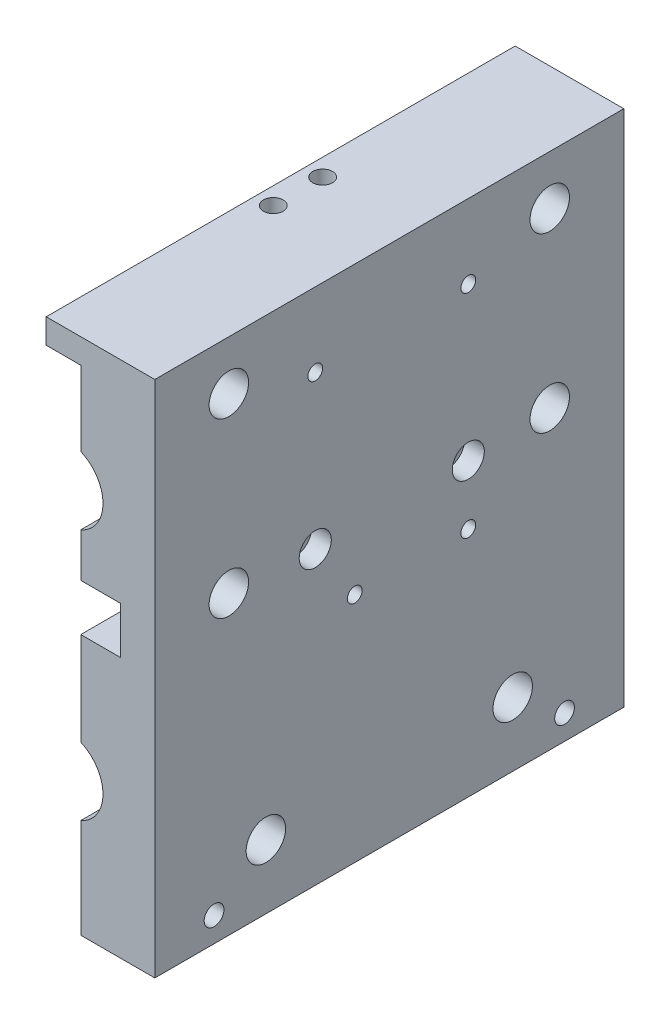
SolidWorks part; units mm, degrees
material "ABS"
ref_plane "Front Plane" through (0, 0, 0) normal (0, 0, 1) x (1, 0, 0)
ref_plane "Top Plane" through (0, 0, 0) normal (0, 1, 0) x (1, 0, 0)
ref_plane "Right Plane" through (0, 0, 0) normal (1, 0, 0) x (0, 0, -1)
sketch "Sketch1" plane through (0, 0, 0) normal (0, 0, 1) x (1, 0, 0)
  line L0 (0, 0) -> (0, -37.75)
  line L1 (0, -37.75) -> (8, -37.75)
  line L2 (8, -37.75) -> (8, -47.25)
  line L3 (8, -47.25) -> (0, -47.25)
  line L4 (0, -47.25) -> (0, -100)
  line L5 (0, -100) -> (15, -100)
  line L6 (15, -100) -> (15, 5)
  line L7 (15, 5) -> (-7, 5)
  line L8 (-7, 5) -> (-7, 0)
  line L9 (-7, 0) -> (0, 0)
  dimension "D1" = 15
  dimension "D2" = 8
  dimension "D3" = 7
  dimension "D4" = 5
  dimension "D5" = 37.75
  dimension "D6" = 105
  dimension "D7" = 9.5
extrude "Boss-Extrude1" add sketch "Sketch1" along normal blind 95
ref_plane "Plan6" through (0, -47.5, 0) normal (0, 1, 0) x (1, 0, 0)
ref_plane "Plan3" through (0, 0, 47.5) normal (0, 0, -1) x (-1, 0, 0)
sketch "Sketch2" plane through (0, 0, 0) normal (-1, 0, 0) x (0, 0, 1)
  line L0 (95, 5) -> (0, 5) construction
  line L2 (47.5, 5) -> (47.5, -173.9913) construction
  line L3 (12.1, -47.5) -> (-12.1, -47.5) construction
  circle A1 centre (62.5, -41) radius 2
  circle A2 centre (31.5, -41) radius 2
  dimension "D2" = 4
  dimension "D4" = 31
  dimension "D5" = 15
  dimension "D6" = 6.5
extrude "Cut-Extrude1 3dprinter4" cut sketch "Sketch2" against normal through all
sketch "Esquisse1" plane through (15, 0, 0) normal (1, 0, 0) x (0, 0, -1)
  line L2 (-47.5, -12.1) -> (-47.5, 12.1) construction
  line L3 (12.1, -47.5) -> (-12.1, -47.5) construction
  circle A0 centre (-62.5, -10) radius 1.5
  circle A1 centre (-31.5, -10) radius 1.5
  circle A4 centre (-54.5, -53) radius 1.5
  circle A5 centre (-31.5, -53) radius 1.5
  dimension "D1" = 15
  dimension "D2" = 37.5
  dimension "D3" = 31
  dimension "D4" = 43
  dimension "D5" = 3
  dimension "D6" = 8
  dimension "D7" = 23
extrude "Enlèv. mat.-Extru.1 3d printer" cut sketch "Esquisse1" against normal through all
sketch "Esquisse2" plane through (0, 0, 0) normal (-1, 0, 0) x (0, 0, 1)
  circle A0 centre (62.5, -10) radius 2.5
  circle A1 centre (31.5, -10) radius 2.5
  dimension "D1" = 5
extrude "Enlèv. mat.-Extru.2" cut sketch "Esquisse2" against normal blind 3 and the other way through all
sketch "Esquisse3" plane through (15, 0, 0) normal (1, 0, 0) x (0, 0, -1)
  circle A1 centre (-31.5, -41) radius 3.25
  circle A2 centre (-62.5, -41) radius 3.25
  dimension "D1" = 6.5
extrude "Enlèv. mat.-Extru.3" cut sketch "Esquisse3" against normal blind 4
sketch "Esquisse4" plane through (15, 0, 0) normal (1, 0, 0) x (0, 0, -1)
  line L0 (-95, -100) -> (-95, 5) construction
  line L1 (0, -100) -> (0, 5) construction
  line L2 (-95, -100) -> (0, -100) construction
  circle A0 centre (-83, -95) radius 2
  circle A1 centre (-12, -95) radius 2
  circle A2 centre (-12, -95) radius 3.25
  circle A3 centre (-83, -95) radius 3.25
  dimension "D1" = 4
  dimension "D2" = 12
  dimension "D3" = 12
  dimension "D4" = 5
  dimension "D5" = 6.5
extrude "Enlèv. mat.-Extru.4" cut sketch "Esquisse4" against normal through all contours A0 | A1
sketch "Esquisse8" plane through (0, 0, 0) normal (0, 0, -1) x (-1, 0, 0)
  line L1 (-15, -100) -> (-15, 5) construction
  line L4 (12.1, -47.5) -> (-12.1, -47.5) construction
  circle A0 centre (3, -22) radius 7.5
  circle A1 centre (3, -73) radius 7.5
  dimension "D1" = 25.5
  dimension "D2" = 18
  dimension "D3" = 15
  dimension "D4" = 25.5
extrude "Enlèv. mat.-Extru.9" cut sketch "Esquisse8" against normal through all
sketch "Esquisse9" plane through (15, 0, 0) normal (1, 0, 0) x (0, 0, -1)
  line L0 (0, -100) -> (0, 5) construction
  line L1 (-95, 5) -> (0, 5) construction
  circle A0 centre (-15, -5) radius 4
  circle A1 centre (-80, -5) radius 4
  circle A2 centre (-80, -40) radius 4
  circle A3 centre (-15, -40) radius 4
  circle A4 centre (-22.5, -87) radius 4
  circle A5 centre (-72.5, -87) radius 4
  dimension "D1" = 8
  dimension "D2" = 15
  dimension "D3" = 10
  dimension "D6" = 65
  dimension "D7" = 35
  dimension "D8" = 82
  dimension "D9" = 7.5
  dimension "D11" = 50
  dimension "D4" = 2
  dimension "D5" = 2
  dimension "D10" = 2
extrude "Enlèv. mat.-Extru.10cnc trous" cut sketch "Esquisse9" against normal through all
sketch "Esquisse10" plane through (0, 0, 0) normal (0, -1, 0) x (1, 0, 0)
  line L0 (-12.1, 47.5) -> (12.1, 47.5) construction
  line L1 (-7, 95) -> (-7, 0) construction
  circle A0 centre (-3.5, 52.5) radius 2
  circle A1 centre (-3.5, 42.5) radius 2
  point P8 (0, 0)
  dimension "D1" = 4
  dimension "D2" = 5
  dimension "D3" = 5
  dimension "D4" = 3.5
extrude "Enlèv. mat.-Extru.10" cut sketch "Esquisse10" against normal through all
sketch "Esquisse11" plane through (0, 0, 0) normal (-1, 0, 0) x (0, 0, 1)
  circle A0 centre (54.5, -53) radius 2.5
  circle A1 centre (31.5, -53) radius 2.5
  dimension "D1" = 5
extrude "Enlèv. mat.-Extru.11" cut sketch "Esquisse11" against normal blind 5
